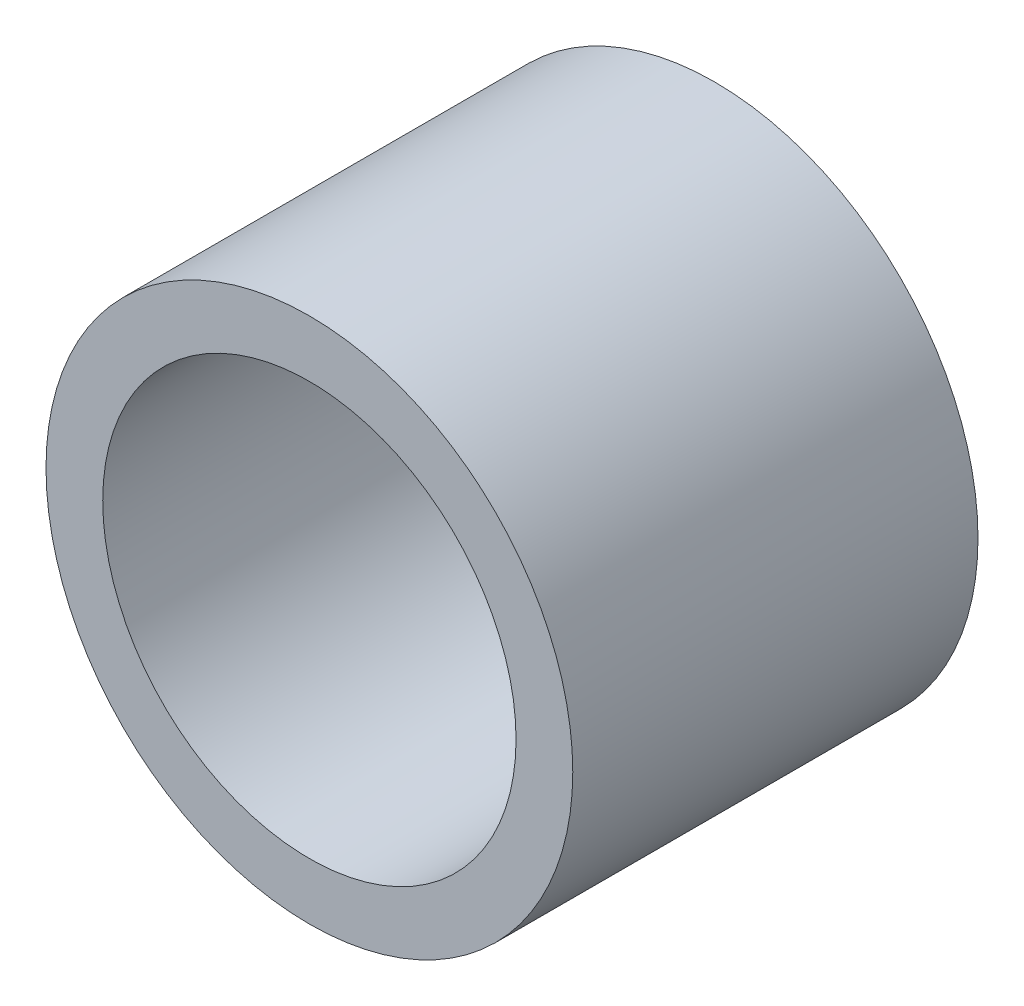
SolidWorks part; units mm, degrees
ref_plane "Front Plane" through (0, 0, 0) normal (0, 0, 1) x (1, 0, 0)
ref_plane "Top Plane" through (0, 0, 0) normal (0, 1, 0) x (1, 0, 0)
ref_plane "Right Plane" through (0, 0, 0) normal (1, 0, 0) x (0, 0, -1)
sketch "Sketch1" plane through (0, 0, 0) normal (0, 0, 1) x (1, 0, 0)
  circle A0 centre (0, 0) radius 2.55
  circle A1 centre (0, 0) radius 3.25
  dimension "D1" = 5.1
  dimension "D2" = 6.5
extrude "Boss-Extrude1" add sketch "Sketch1" along normal blind 5
